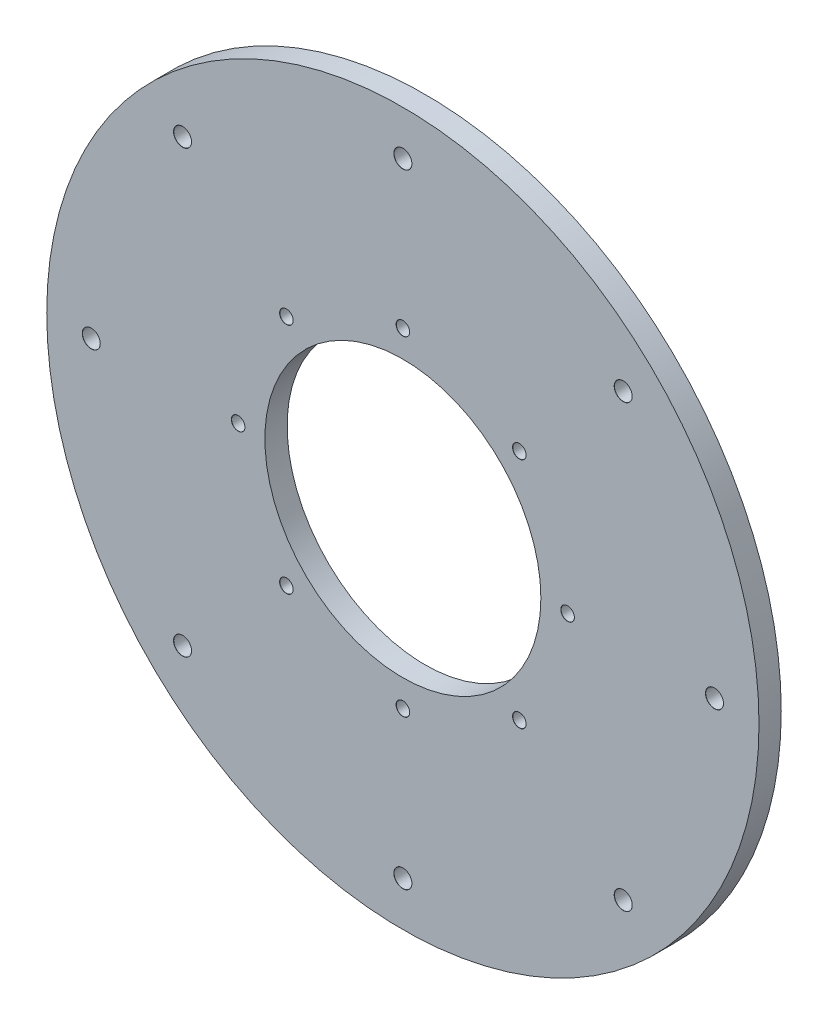
SolidWorks part; units mm, degrees
ref_plane "Front Plane" through (0, 0, 0) normal (0, 0, 1) x (1, 0, 0)
ref_plane "Top Plane" through (0, 0, 0) normal (0, 1, 0) x (1, 0, 0)
ref_plane "Right Plane" through (0, 0, 0) normal (1, 0, 0) x (0, 0, -1)
sketch "Sketch2" plane through (0, 0, 0) normal (0, 0, 1) x (1, 0, 0)
  line L0 (0, 0) -> (0, 90.7247) construction
  circle A0 centre (0, 0) radius 80
  circle A1 centre (0, 0) radius 31
  point P0 (0, 0)
  point P4 (0, 70)
  point P5 (49.4975, 49.4975)
  point P8 (70, 0)
  point P9 (49.4975, -49.4975)
  point P10 (0, -70)
  point P11 (-49.4975, -49.4975)
  point P12 (-70, 0)
  point P13 (-49.4975, 49.4975)
  point P14 (0, 0)
  dimension "D3" = 160
  dimension "D4" = 62
  dimension "D1" = 70
  dimension "D2" = 8
extrude "Boss-Extrude1" add sketch "Sketch2" along normal blind 5
sketch "Sketch9" plane through (0, 0, 0) normal (0, 0, 1) x (1, 0, 0)
  line L0 (0, 0) -> (0, 90.7247) construction
  circle A0 centre (0, 0) radius 80
  circle A1 centre (0, 0) radius 31
  point P0 (0, 0)
  point P4 (0, 70)
  point P5 (49.4975, 49.4975)
  point P8 (70, 0)
  point P9 (49.4975, -49.4975)
  point P10 (0, -70)
  point P11 (-49.4975, -49.4975)
  point P12 (-70, 0)
  point P13 (-49.4975, 49.4975)
  point P14 (0, 0)
  dimension "D3" = 160
  dimension "D4" = 62
  dimension "D1" = 70
  dimension "D2" = 8
hole_wizard "Ø4.0mm Dowel Hole1" positions "Sketch10" profile "Sketch11" hole size "Ø4.0" standard "ISO"
sketch "Sketch10" plane through (0, 0, 5) normal (0, 0, 1) x (1, 0, 0)
  point P0 (0, 70)
  point P3 (-49.4975, 49.4975)
  point P6 (-70, 0)
  point P9 (-49.4975, -49.4975)
  point P12 (0, -70)
  point P15 (49.4975, -49.4975)
  point P18 (70, 0)
  point P21 (49.4975, 49.4975)
sketch "Sketch11" plane through (0, 70, 5) normal (1, 0, 0) x (0, -1, 0)
  line L0 (0, 0) -> (0, 6.2007)
  line L1 (0, 6.2007) -> (2, 4.999)
  line L2 (2, 4.999) -> (2, 0.025)
  line L3 (2, 0.025) -> (2.025, 0)
  line L5 (2.025, 0) -> (0, 0)
  line L6 (-2, 0.025) -> (-2.025, 0) construction
  line L10 (0, 6.2007) -> (-2, 4.999) construction
  line L11 (0, -6.35) -> (0, 107.95) construction
  dimension "Hole Dia." = 4
  dimension "Hole Depth" = 4.999
  dimension "Near C'Sink Dia." = 4.05
  dimension "Near C'Sink Angle" = 90
  dimension "Drill Angle" = 118
sketch "Sketch13" plane through (0, 0, 0) normal (0, 0, 1) x (1, 0, 0)
  line L0 (0, 0) -> (0, 102.9505) construction
  point P3 (0, 37)
  point P4 (26.163, 26.163)
  point P7 (37, 0)
  point P8 (26.163, -26.163)
  point P9 (0, -37)
  point P10 (-26.163, -26.163)
  point P11 (-37, 0)
  point P12 (-26.163, 26.163)
  point P13 (0, 0)
  dimension "D1" = 37
  dimension "D2" = 8
hole_wizard "Ø3.0mm Dowel Hole1" positions "Sketch14" profile "Sketch15" hole size "Ø3.0" standard "ISO"
sketch "Sketch14" plane through (0, 0, 5) normal (0, 0, 1) x (1, 0, 0)
  point P0 (0, 37)
  point P3 (-26.163, 26.163)
  point P6 (-37, 0)
  point P9 (-26.163, -26.163)
  point P12 (0, -37)
  point P15 (26.163, -26.163)
  point P18 (37, 0)
  point P21 (26.163, 26.163)
sketch "Sketch15" plane through (0, 37, 5) normal (1, 0, 0) x (0, -1, 0)
  line L0 (0, 0) -> (0, 5.9003)
  line L1 (0, 5.9003) -> (1.5, 4.999)
  line L2 (1.5, 4.999) -> (1.5, 0.025)
  line L3 (1.5, 0.025) -> (1.525, 0)
  line L5 (1.525, 0) -> (0, 0)
  line L6 (-1.5, 0.025) -> (-1.525, 0) construction
  line L10 (0, 5.9003) -> (-1.5, 4.999) construction
  line L11 (0, -6.35) -> (0, 107.95) construction
  dimension "Hole Dia." = 3
  dimension "Hole Depth" = 4.999
  dimension "Near C'Sink Dia." = 3.05
  dimension "Near C'Sink Angle" = 90
  dimension "Drill Angle" = 118
